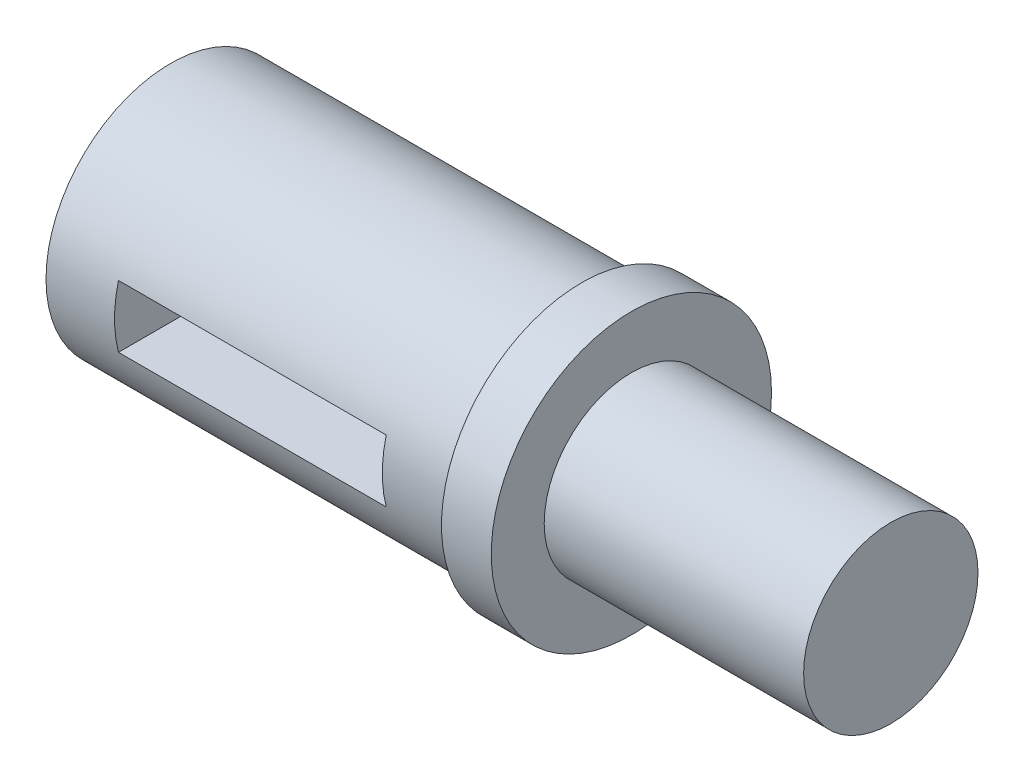
SolidWorks part; units mm, degrees
ref_plane "Front Plane" through (0, 0, 0) normal (0, 0, 1) x (1, 0, 0)
ref_plane "Top Plane" through (0, 0, 0) normal (0, 1, 0) x (1, 0, 0)
ref_plane "Right Plane" through (0, 0, 0) normal (1, 0, 0) x (0, 0, -1)
sketch "Sketch1" plane through (0, 0, 0) normal (0, 1, 0) x (1, 0, 0)
  line L0 (-55.4857, 0) -> (-55.4857, 20)
  line L1 (-55.4857, 20) -> (10.5143, 20)
  line L2 (10.5143, 20) -> (10.5143, 22.5)
  line L3 (10.5143, 22.5) -> (18.5143, 22.5)
  line L4 (18.5143, 22.5) -> (18.5143, 14)
  line L5 (18.5143, 14) -> (60.1714, 14)
  line L6 (60.1714, 14) -> (60.1714, 0)
  line L7 (60.1714, 0) -> (-55.4857, 0)
  dimension "D1" = 20
  dimension "D2" = 66
  dimension "D3" = 8
  dimension "D4" = 14
  dimension "D5" = 22.5
revolve "Revolve1" add sketch "Sketch1" angle 360 about L7
sketch "Sketch2" plane through (0, 0, 0) normal (0, 0, 1) x (1, 0, 0)
  line L0 (-55.4857, 20) -> (-55.4857, -20) construction
  line L1 (-44.4857, 5) -> (-1.4857, 5)
  line L2 (-44.4857, 5) -> (-44.4857, -5)
  line L3 (-44.4857, -5) -> (-1.4857, -5)
  line L4 (-1.4857, 5) -> (-1.4857, -5)
  line L5 (10.5143, 20) -> (-55.4857, 20) construction
  dimension "D1" = 10
  dimension "D2" = 43
  dimension "D3" = 11
  dimension "D4" = 15
extrude "Cut-Extrude1" cut sketch "Sketch2" against normal through all both and the other way through all
